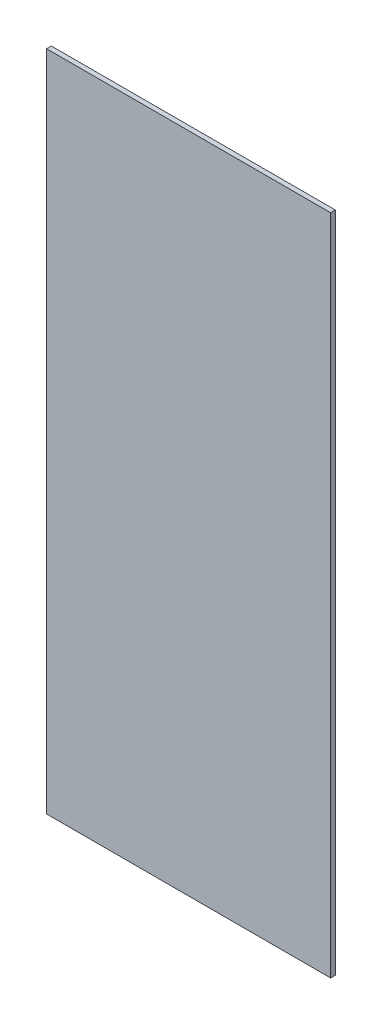
SolidWorks part; units mm, degrees
ref_plane "Front Plane" through (0, 0, 0) normal (0, 0, 1) x (1, 0, 0)
ref_plane "Top Plane" through (0, 0, 0) normal (0, 1, 0) x (1, 0, 0)
ref_plane "Right Plane" through (0, 0, 0) normal (1, 0, 0) x (0, 0, -1)
sketch "Sketch1" plane through (0, 0, 0) normal (0, 0, 1) x (1, 0, 0)
  line L1 (0, 0) -> (300, 0)
  line L2 (0, 0) -> (0, 700)
  line L3 (0, 700) -> (300, 700)
  line L4 (300, 0) -> (300, 700)
  dimension "D1" = 300
  dimension "D2" = 700
extrude "Boss-Extrude1" add sketch "Sketch1" along normal blind 5
